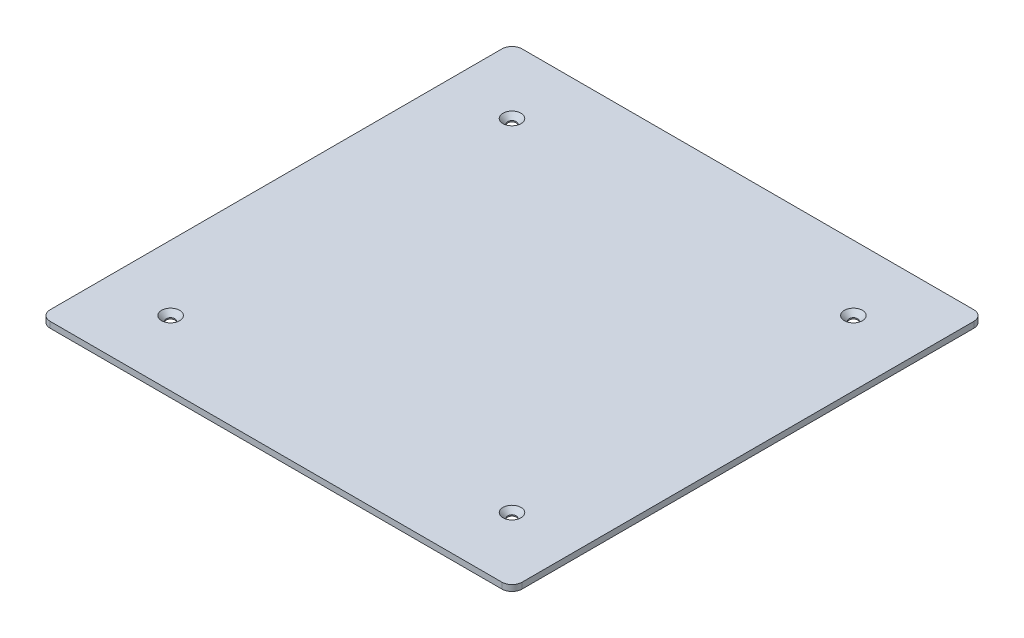
SolidWorks part; units mm, degrees
ref_plane "Front Plane" through (0, 0, 0) normal (0, 0, 1) x (1, 0, 0)
ref_plane "Top Plane" through (0, 0, 0) normal (0, 1, 0) x (1, 0, 0)
ref_plane "Right Plane" through (0, 0, 0) normal (1, 0, 0) x (0, 0, -1)
sketch "Sketch1" plane through (0, 0, 0) normal (0, 1, 0) x (1, 0, 0)
  line L5 (-117.5, 117.5) -> (117.5, -117.5)
  line L6 (-117.5, -117.5) -> (117.5, -117.5)
  line L7 (-117.5, -117.5) -> (-117.5, 117.5)
  line L8 (-117.5, 117.5) -> (117.5, 117.5)
  line L9 (117.5, -117.5) -> (117.5, 117.5)
  line L10 (0, 0) -> (0, 155.1648)
  line L11 (0, 0) -> (-148.5142, -85.7447)
  line L12 (0, 0) -> (152.0297, -87.7744)
  point P12 (0, 0)
  dimension "D5" = 235
  dimension "D6" = 235
  dimension "D7" = 120
  dimension "D8" = 120
extrude "Boss-Extrude1" add sketch "Sketch1" along normal blind 3 contours L11 L5 L7 | L5 L10 L8 | L10 L12 L9 L8 | L12 L5 L9 | L5 L11 L7 L6
sketch "Sketch2" plane through (0, 0, 0) normal (0, -1, 0) x (1, 0, 0)
  line L1 (85, -85) -> (-85, -85) construction
  line L2 (85, -85) -> (85, 85) construction
  line L3 (85, 85) -> (-85, 85) construction
  line L4 (-85, -85) -> (-85, 85) construction
  line L5 (85, -85) -> (-85, 85) construction
  line L6 (85, 85) -> (-85, -85) construction
  circle A0 centre (85, -85) radius 2.1
  circle A1 centre (-85, -85) radius 2.1
  circle A2 centre (-85, 85) radius 2.1
  circle A3 centre (85, 85) radius 2.1
  point P0 (0, 0)
  dimension "D3" = 4.2
  dimension "D1" = 170
  dimension "D2" = 170
extrude "Cut-Extrude1" cut sketch "Sketch2" against normal blind 3 contours A0 | A2 | A3 | A1
fillet "Fillet1" radius 5 4 edges at (-117.5, 1.5, 117.5) (-117.5, 1.5, -117.5) (117.5, 1.5, -117.5) (117.5, 1.5, 117.5)
sketch "Sketch3" plane through (0, 0, 0) normal (0, -1, 0) x (1, 0, 0)
  line L0 (0, 0) -> (0, -155.1648)
  line L1 (0, 0) -> (152.0297, 87.7744)
  line L2 (0, 0) -> (-148.5142, 85.7447)
chamfer "Chamfer1" distance 2.4 angle 45 4 edges at (-85, 3, 82.9) (85, 3, 82.9) (85, 3, -87.1) (-85, 3, -87.1)
